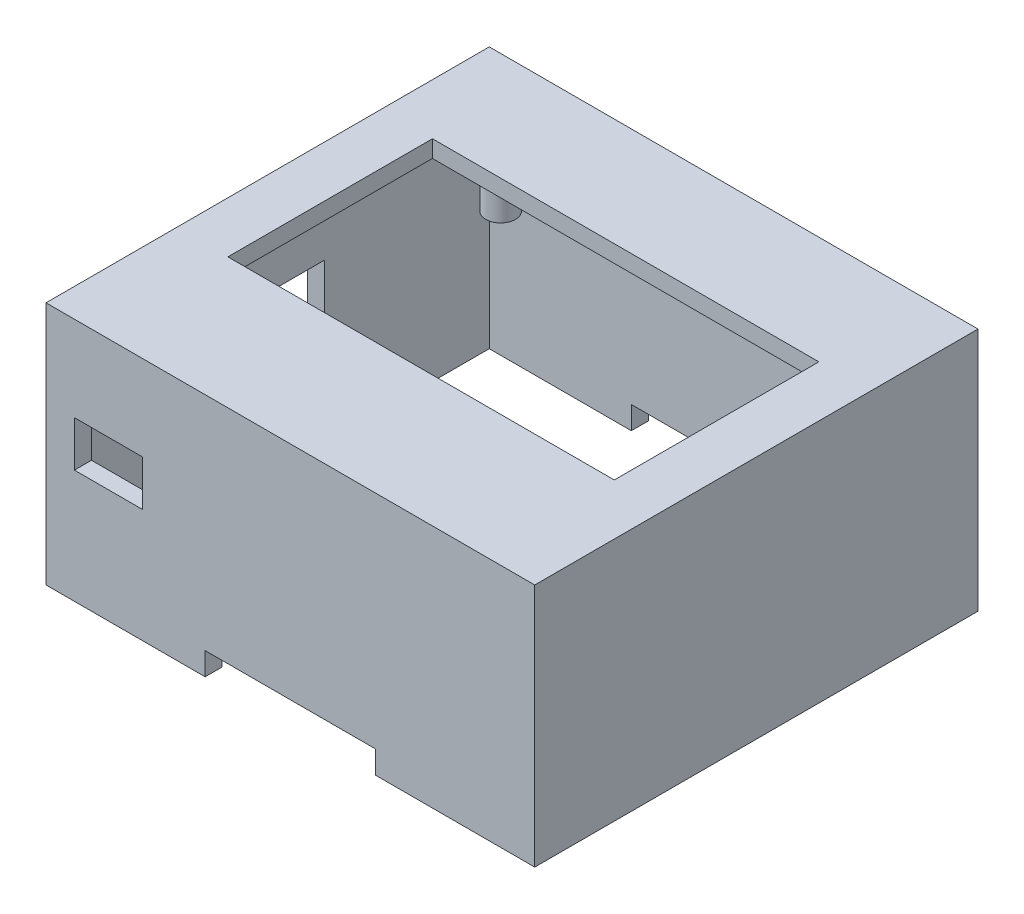
SolidWorks part; units mm, degrees
ref_plane "정면" through (0, 0, 0) normal (0, 0, 1) x (1, 0, 0)
ref_plane "윗면" through (0, 0, 0) normal (0, 1, 0) x (1, 0, 0)
ref_plane "우측면" through (0, 0, 0) normal (1, 0, 0) x (0, 0, -1)
sketch "스케치1" plane through (0, 0, 0) normal (0, 1, 0) x (1, 0, 0)
  line L1 (-21.5, 19.5) -> (21.5, 19.5)
  line L2 (-21.5, 19.5) -> (-21.5, -19.5)
  line L3 (-21.5, -19.5) -> (21.5, -19.5)
  line L4 (21.5, 19.5) -> (21.5, -19.5)
  line L5 (-21.5, 19.5) -> (21.5, -19.5) construction
  line L6 (-21.5, -19.5) -> (21.5, 19.5) construction
  point P0 (0, 0)
  dimension "D1" = 43
  dimension "D2" = 39
extrude "Body" add sketch "스케치1" along normal blind 1.5
sketch "스케치3" plane through (0, 0, 0) normal (0, -1, 0) x (1, 0, 0)
  line L1 (-15, 14) -> (15, 14) construction
  line L2 (-15, 14) -> (-15, -14) construction
  line L3 (-15, -14) -> (15, -14) construction
  line L4 (15, 14) -> (15, -14) construction
  line L5 (-15, 14) -> (15, -14) construction
  line L6 (-15, -14) -> (15, 14) construction
  circle A1 centre (15, 14) radius 1.3
  circle A3 centre (-15, -14) radius 1.3
  point P0 (0, 0)
  point P5 (0, 0)
  dimension "D4" = 2.6
  dimension "D1" = 30
  dimension "D2" = 28
extrude "OLED_pillar" add sketch "스케치3" along normal blind 5
sketch "스케치2" plane through (0, 1.5, 0) normal (0, 1, 0) x (1, 0, 0)
  line L1 (17, -8) -> (17, 10)
  line L2 (17, -8) -> (-17, -8)
  line L3 (-17, -8) -> (-17, 10)
  line L4 (17, 10) -> (-17, 10)
  line L5 (17, -8) -> (-17, 10) construction
  line L6 (-17, -8) -> (17, 10) construction
  point P0 (0, 0)
  point P5 (0, 1)
  dimension "D1" = 1
  dimension "D2" = 34
  dimension "D3" = 18
extrude "OLED_window" cut sketch "스케치2" against normal up to next
sketch "스케치4" plane through (0, 0, 0) normal (0, -1, 0) x (1, 0, 0)
  line L0 (20, 18) -> (-20, 18)
  line L5 (-20, 18) -> (-20, -18)
  line L6 (-20, -18) -> (20, -18)
  line L7 (20, -18) -> (20, 18)
  line L10 (21.5, -19.5) -> (21.5, 19.5)
  line L11 (21.5, 19.5) -> (-21.5, 19.5)
  line L12 (-21.5, 19.5) -> (-21.5, -19.5)
  line L13 (-21.5, -19.5) -> (21.5, -19.5)
  line L14 (21.5, -19.5) -> (21.5, 19.5)
  line L15 (21.5, 19.5) -> (-21.5, 19.5)
  line L16 (-21.5, 19.5) -> (-21.5, -19.5)
  line L17 (-21.5, -19.5) -> (21.5, -19.5)
  point P0 (0, 0)
  dimension "D1" = 0
  dimension "D2" = 1.5
extrude "FarmFeelWall" add sketch "스케치4" along normal blind 20
sketch "스케치7" plane through (-21.5, 0, 0) normal (-1, 0, 0) x (0, 0, 1)
  line L1 (8.5, -11) -> (-3.5, -11)
  line L2 (8.5, -11) -> (8.5, -6)
  line L3 (8.5, -6) -> (-3.5, -6)
  line L4 (-3.5, -11) -> (-3.5, -6)
  line L5 (8.5, -11) -> (-3.5, -6) construction
  line L6 (8.5, -6) -> (-3.5, -11) construction
  point P0 (2.5, -8.5)
  dimension "D1" = 2.5
  dimension "D2" = 8.5
  dimension "D3" = 12
  dimension "D4" = 5
extrude "micro5pin_window" cut sketch "스케치7" against normal up to next
sketch "스케치9" plane through (0, 0, 19.5) normal (0, 0, 1) x (1, 0, 0)
  line L1 (-13, -10) -> (-19, -10)
  line L2 (-13, -10) -> (-13, -6)
  line L3 (-13, -6) -> (-19, -6)
  line L4 (-19, -10) -> (-19, -6)
  line L5 (-13, -10) -> (-19, -6) construction
  line L6 (-13, -6) -> (-19, -10) construction
  point P0 (-16, -8)
  dimension "D1" = 8
  dimension "D2" = 16
  dimension "D3" = 6
  dimension "D4" = 4
extrude "reset_window" cut sketch "스케치9" against normal up to next
sketch "스케치10" plane through (0, -20, 0) normal (0, -1, 0) x (1, 0, 0)
  line L0 (-21.5, -19.5) -> (21.5, -19.5) construction
  line L1 (-7.5, 19.5) -> (7.5, 19.5)
  line L2 (-7.5, 19.5) -> (-7.5, -19.5)
  line L3 (-7.5, -19.5) -> (7.5, -19.5)
  line L4 (7.5, 19.5) -> (7.5, -19.5)
  line L5 (-7.5, 19.5) -> (7.5, -19.5) construction
  line L6 (-7.5, -19.5) -> (7.5, 19.5) construction
  line L7 (21.5, -19.5) -> (21.5, 19.5) construction
  line L11 (21.5, 7.5) -> (21.5, -7.5)
  point P0 (0, 0)
  point P8 (0, 0)
  line M9 (-21.5, -19.5) -> (21.5, -19.5)
  line M11 (21.5, 19.5) -> (-21.5, 19.5)
  line M13 (-20, 18) -> (20, 18)
  line M15 (20, -18) -> (-20, -18)
  dimension "D1" = 15
extrude "컷-돌출1" cut sketch "스케치10" against normal blind 2 contours L4 L2 M15 M9 | L4 L2 M11 M13
